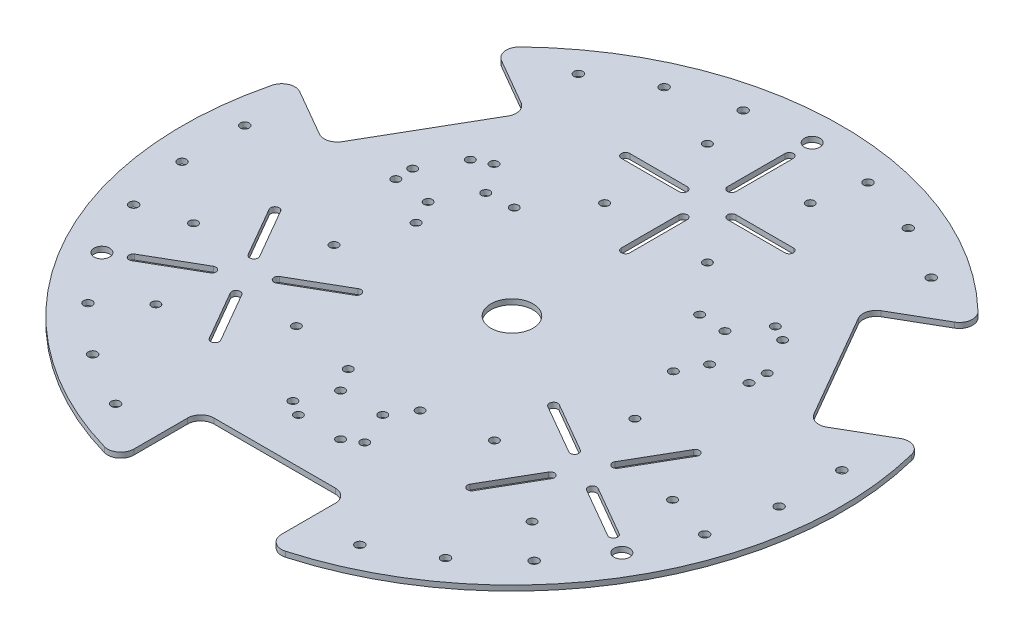
SolidWorks part; units mm, degrees
ref_plane "Front Plane" through (0, 0, 0) normal (0, 0, 1) x (1, 0, 0)
ref_plane "Top Plane" through (0, 0, 0) normal (0, 1, 0) x (1, 0, 0)
ref_plane "Right Plane" through (0, 0, 0) normal (1, 0, 0) x (0, 0, -1)
sketch "Sketch1" plane through (0, 0, 0) normal (0, 1, 0) x (1, 0, 0)
  line L0 (0, 0) -> (0, 125) construction
  line L1 (0, 0) -> (-17.3205, 10) construction
  line L2 (-89.4423, 25.0814) -> (-66.4423, 64.9186)
  line L3 (-68.2724, 71.7487) -> (-91.5024, 85.1605)
  line L4 (-96.2724, 23.2513) -> (-119.5024, 36.6631)
  line L5 (96.2724, 23.2513) -> (119.5024, 36.6631)
  line L6 (66.4423, 64.9186) -> (89.4423, 25.0814)
  line L7 (68.2724, 71.7487) -> (91.5024, 85.1605)
  line L8 (-28, -95) -> (-28, -121.8236)
  line L9 (23, -90) -> (-23, -90)
  line L10 (28, -95) -> (28, -121.8236)
  line L11 (-13.625, -48.465) -> (13.625, -48.465) construction
  line L12 (0, 0) -> (77.9423, 45) construction
  line L13 (0, 0) -> (-108.2532, -62.5) construction
  line L14 (-72.1832, -41.675) -> (-91.0626, -52.575) construction
  line L15 (-71.3832, -43.0606) -> (-90.2626, -53.9606)
  line L16 (-72.9832, -40.2894) -> (-91.8626, -51.1894)
  line L17 (-37.3257, -21.55) -> (-56.205, -32.45) construction
  line L18 (-36.5257, -22.9356) -> (-55.405, -33.8356)
  line L19 (-38.1257, -20.1644) -> (-57.005, -31.0644)
  line L20 (-72.1832, -41.675) -> (-56.205, -32.45) construction
  line L21 (-72.1832, -41.675) -> (-56.205, -32.45) construction
  line L22 (-68.8066, -29.0734) -> (-79.7066, -10.1941) construction
  line L23 (-70.1923, -29.8734) -> (-81.0923, -10.9941)
  line L24 (-67.421, -28.2734) -> (-78.321, -9.3941)
  line L25 (-56.205, -32.45) -> (-37.3257, -21.55) construction
  line L26 (-57.005, -31.0644) -> (-38.1257, -20.1644)
  line L27 (-55.405, -33.8356) -> (-36.5257, -22.9356)
  line L28 (-59.5816, -45.0516) -> (-48.6816, -63.9309) construction
  line L29 (-58.196, -44.2516) -> (-47.296, -63.1309)
  line L30 (-60.9673, -45.8516) -> (-50.0673, -64.7309)
  line L31 (0, 83.35) -> (0, 105.15) construction
  line L32 (-1.6, 83.35) -> (-1.6, 105.15)
  line L33 (1.6, 83.35) -> (1.6, 105.15)
  line L34 (0, 43.1) -> (0, 64.9) construction
  line L35 (-1.6, 43.1) -> (-1.6, 64.9)
  line L36 (1.6, 43.1) -> (1.6, 64.9)
  line L37 (9.225, 74.125) -> (31.025, 74.125) construction
  line L38 (9.225, 75.725) -> (31.025, 75.725)
  line L39 (9.225, 72.525) -> (31.025, 72.525)
  line L40 (-9.225, 74.125) -> (-31.025, 74.125) construction
  line L41 (-9.225, 72.525) -> (-31.025, 72.525)
  line L42 (-9.225, 75.725) -> (-31.025, 75.725)
  line L43 (72.1832, -41.675) -> (91.0626, -52.575) construction
  line L44 (72.9832, -40.2894) -> (91.8626, -51.1894)
  line L45 (71.3832, -43.0606) -> (90.2626, -53.9606)
  line L46 (37.3257, -21.55) -> (56.205, -32.45) construction
  line L47 (38.1257, -20.1644) -> (57.005, -31.0644)
  line L48 (36.5257, -22.9356) -> (55.405, -33.8356)
  line L49 (59.5816, -45.0516) -> (48.6816, -63.9309) construction
  line L50 (60.9673, -45.8516) -> (50.0673, -64.7309)
  line L51 (58.196, -44.2516) -> (47.296, -63.1309)
  line L52 (68.8066, -29.0734) -> (79.7066, -10.1941) construction
  line L53 (67.421, -28.2734) -> (78.321, -9.3941)
  line L54 (70.1923, -29.8734) -> (81.0923, -10.9941)
  line L55 (-49.8802, 55.605) -> (-73.0954, 15.395)
  line L56 (0, 0) -> (0, -90.0676) construction
  line L59 (13.625, -69.465) -> (-13.625, -69.465) construction
  line L60 (-13.625, -48.465) -> (-13.625, -69.465) construction
  line L61 (13.625, -48.465) -> (13.625, -69.465) construction
  line L62 (13.625, -71.065) -> (-13.625, -71.065) construction
  line L63 (8, -57) -> (-8, -57) construction
  line L64 (8, -57) -> (8, -73) construction
  line L65 (8, -73) -> (-8, -73) construction
  line L66 (-8, -57) -> (-8, -73) construction
  line L67 (8, -57) -> (-8, -73) construction
  line L68 (8, -73) -> (-8, -57) construction
  line L69 (8, -74.6) -> (-8, -74.6) construction
  circle A0 centre (0, 0) radius 8
  arc A1 (-119.5024, 36.6631) -> (-28, -121.8236) centre (0, 0) ccw
  circle A2 centre (0, 113.85) radius 2.95
  circle A3 centre (98.597, -56.925) radius 2.95
  circle A4 centre (-98.597, -56.925) radius 2.95
  circle A5 centre (0, 113.85) radius 1.675
  circle A6 centre (0, 0) radius 90 construction
  arc A7 (-89.4423, 25.0814) -> (-96.2724, 23.2513) centre (-93.7724, 27.5814) cw
  arc A8 (-66.4423, 64.9186) -> (-68.2724, 71.7487) centre (-70.7724, 67.4186) ccw
  arc A9 (89.4423, 25.0814) -> (96.2724, 23.2513) centre (93.7724, 27.5814) ccw
  arc A10 (66.4423, 64.9186) -> (68.2724, 71.7487) centre (70.7724, 67.4186) cw
  arc A11 (-23, -90) -> (-28, -95) centre (-23, -95) ccw
  arc A12 (23, -90) -> (28, -95) centre (23, -95) cw
  arc A13 (91.5024, 85.1605) -> (-91.5024, 85.1605) centre (0, 0) ccw
  arc A14 (28, -121.8236) -> (119.5024, 36.6631) centre (0, 0) ccw
  circle A15 centre (23.6707, 111.3621) radius 1.675
  circle A16 centre (46.307, 104.0072) radius 1.675
  circle A17 centre (66.9194, 92.1066) radius 1.675
  circle A18 centre (84.607, 76.1805) radius 1.675
  circle A19 centre (98.597, 56.925) radius 1.675
  circle A20 centre (108.2778, 35.1816) radius 1.675
  circle A21 centre (113.2263, 11.9006) radius 1.675
  circle A22 centre (113.2263, -11.9006) radius 1.675
  circle A23 centre (108.2778, -35.1816) radius 1.675
  circle A25 centre (84.607, -76.1805) radius 1.675
  circle A26 centre (66.9194, -92.1066) radius 1.675
  circle A27 centre (46.307, -104.0072) radius 1.675
  circle A28 centre (23.6707, -111.3621) radius 1.675
  circle A29 centre (0, -113.85) radius 1.675
  circle A30 centre (-23.6707, -111.3621) radius 1.675
  circle A31 centre (-46.307, -104.0072) radius 1.675
  circle A32 centre (-66.9194, -92.1066) radius 1.675
  circle A33 centre (-84.607, -76.1805) radius 1.675
  circle A35 centre (-108.2778, -35.1816) radius 1.675
  circle A36 centre (-113.2263, -11.9006) radius 1.675
  circle A37 centre (-113.2263, 11.9006) radius 1.675
  circle A38 centre (-108.2778, 35.1816) radius 1.675
  circle A39 centre (-98.597, 56.925) radius 1.675
  circle A40 centre (-84.607, 76.1805) radius 1.675
  circle A41 centre (-66.9194, 92.1066) radius 1.675
  circle A42 centre (-46.307, 104.0072) radius 1.675
  circle A43 centre (-23.6707, 111.3621) radius 1.675
  circle A44 centre (-98.597, -56.925) radius 1.675 [skipped]
  circle A45 centre (98.597, -56.925) radius 1.675 [skipped]
  circle A46 centre (0, 0) radius 106.75 construction
  arc A47 (-71.3832, -43.0606) -> (-72.9832, -40.2894) centre (-72.1832, -41.675) ccw
  arc A48 (-91.8626, -51.1894) -> (-90.2626, -53.9606) centre (-91.0626, -52.575) ccw
  circle A49 centre (0, 0) radius 66.5 construction
  arc A50 (-36.5257, -22.9356) -> (-38.1257, -20.1644) centre (-37.3257, -21.55) ccw
  arc A51 (-57.005, -31.0644) -> (-55.405, -33.8356) centre (-56.205, -32.45) ccw
  circle A52 centre (-64.1941, -37.0625) radius 2 construction
  arc A53 (-70.1923, -29.8734) -> (-67.421, -28.2734) centre (-68.8066, -29.0734) ccw
  arc A54 (-78.321, -9.3941) -> (-81.0923, -10.9941) centre (-79.7066, -10.1941) ccw
  arc A55 (-57.005, -31.0644) -> (-55.405, -33.8356) centre (-56.205, -32.45) ccw
  arc A56 (-36.5257, -22.9356) -> (-38.1257, -20.1644) centre (-37.3257, -21.55) ccw
  arc A57 (-58.196, -44.2516) -> (-60.9673, -45.8516) centre (-59.5816, -45.0516) ccw
  arc A58 (-50.0673, -64.7309) -> (-47.296, -63.1309) centre (-48.6816, -63.9309) ccw
  arc A59 (-1.6, 83.35) -> (1.6, 83.35) centre (0, 83.35) ccw
  arc A60 (1.6, 105.15) -> (-1.6, 105.15) centre (0, 105.15) ccw
  arc A61 (-1.6, 43.1) -> (1.6, 43.1) centre (0, 43.1) ccw
  arc A62 (1.6, 64.9) -> (-1.6, 64.9) centre (0, 64.9) ccw
  arc A63 (9.225, 75.725) -> (9.225, 72.525) centre (9.225, 74.125) ccw
  arc A64 (31.025, 72.525) -> (31.025, 75.725) centre (31.025, 74.125) ccw
  arc A65 (-9.225, 72.525) -> (-9.225, 75.725) centre (-9.225, 74.125) ccw
  arc A66 (-31.025, 75.725) -> (-31.025, 72.525) centre (-31.025, 74.125) ccw
  arc A67 (72.9832, -40.2894) -> (71.3832, -43.0606) centre (72.1832, -41.675) ccw
  arc A68 (90.2626, -53.9606) -> (91.8626, -51.1894) centre (91.0626, -52.575) ccw
  arc A69 (38.1257, -20.1644) -> (36.5257, -22.9356) centre (37.3257, -21.55) ccw
  arc A70 (55.405, -33.8356) -> (57.005, -31.0644) centre (56.205, -32.45) ccw
  arc A71 (60.9673, -45.8516) -> (58.196, -44.2516) centre (59.5816, -45.0516) ccw
  arc A72 (47.296, -63.1309) -> (50.0673, -64.7309) centre (48.6816, -63.9309) ccw
  arc A73 (67.421, -28.2734) -> (70.1923, -29.8734) centre (68.8066, -29.0734) ccw
  arc A74 (81.0923, -10.9941) -> (78.321, -9.3941) centre (79.7066, -10.1941) ccw
  circle A75 centre (0, 0) radius 100.95 construction
  circle A76 centre (-61.4878, 35.5) radius 5 construction
  circle A77 centre (-90.8316, -29.925) radius 1.6
  circle A78 centre (-57.0566, -10.425) radius 1.6
  circle A79 centre (-37.5566, -44.2) radius 1.6
  circle A80 centre (-71.3316, -63.7) radius 1.6
  circle A81 centre (19.5, 93.625) radius 1.6
  circle A82 centre (19.5, 54.625) radius 1.6
  circle A83 centre (-19.5, 54.625) radius 1.6
  circle A84 centre (-19.5, 93.625) radius 1.6
  circle A85 centre (71.3316, -63.7) radius 1.6
  circle A86 centre (37.5566, -44.2) radius 1.6
  circle A87 centre (57.0566, -10.425) radius 1.6
  circle A88 centre (90.8316, -29.925) radius 1.6
  circle A89 centre (0, 0) radius 69.465 construction
  circle A90 centre (-13.625, -48.465) radius 1.6
  circle A91 centre (13.625, -48.465) radius 1.6
  circle A92 centre (13.625, -69.465) radius 1.6
  circle A93 centre (-13.625, -69.465) radius 1.6
  circle A94 centre (-35.1594, 36.0321) radius 1.6
  circle A95 centre (-48.7844, 12.4329) radius 1.6
  circle A96 centre (-66.971, 22.9329) radius 1.6
  circle A97 centre (-53.346, 46.5321) radius 1.6
  circle A98 centre (48.7844, 12.4329) radius 1.6
  circle A99 centre (35.1594, 36.0321) radius 1.6
  circle A100 centre (53.346, 46.5321) radius 1.6
  circle A101 centre (66.971, 22.9329) radius 1.6
  circle A102 centre (0, 0) radius 73 construction
  circle A103 centre (-8, -73) radius 1.6
  circle A104 centre (-8, -57) radius 1.6
  circle A105 centre (8, -57) radius 1.6
  circle A106 centre (8, -73) radius 1.6
  circle A107 centre (-59.2199, 43.4282) radius 1.6
  circle A108 centre (-45.3634, 35.4282) radius 1.6
  circle A109 centre (-53.3634, 21.5718) radius 1.6
  circle A110 centre (-67.2199, 29.5718) radius 1.6
  circle A111 centre (67.2199, 29.5718) radius 1.6
  circle A112 centre (53.3634, 21.5718) radius 1.6
  circle A113 centre (45.3634, 35.4282) radius 1.6
  circle A114 centre (59.2199, 43.4282) radius 1.6
  point P14 (0, 0)
  point P18 (-77.9423, 45)
  point P22 (-91.9423, 20.7513)
  point P25 (-63.9423, 69.2487)
  point P44 (0, 0)
  point P84 (-81.6229, -47.125)
  point P103 (0, 0)
  point P115 (-46.7654, -27)
  point P129 (-74.2566, -19.6337)
  point P136 (-46.7654, -27)
  point P143 (-54.1316, -54.4913)
  point P148 (-64.1941, -37.0625)
  point P150 (0, 94.25)
  point P157 (0, 54)
  point P164 (20.125, 74.125)
  point P171 (-20.125, 74.125)
  point P178 (81.6229, -47.125)
  point P185 (46.7654, -27)
  point P192 (54.1316, -54.4913)
  point P199 (74.2566, -19.6337)
  point P204 (0, 0)
  point P209 (-61.4878, 35.5)
  point P220 (-64.1941, -37.0625)
  point P237 (0, 0)
  point P245 (0, -65)
  point P264 (0, 0)
  point P295 (0, 0)
  dimension "D1" = 250
  dimension "D2" = 16
  dimension "D3" = 113.85
  dimension "D4" = 3
  dimension "D5" = 3.35
  dimension "D6" = 60
  dimension "D8" = 5
  dimension "D12" = 213.5
  dimension "D13" = 3.2
  dimension "D14" = 21.8
  dimension "D15" = 3.2
  dimension "D16" = 133
  dimension "D18" = 4
  dimension "D20" = 19
  dimension "D21" = 3.2
  dimension "D26" = 138.93
  dimension "D28" = 3.2
  dimension "D31" = 90
  dimension "D32" = 146
  dimension "D35" = 3.2
  dimension "D37" = 3
  dimension "D7" = 56
  dimension "D11" = 60
  dimension "D17" = 21.8
  dimension "D22" = 17.9
  dimension "D23" = 17.9
  dimension "D27" = 21
  dimension "D29" = 27.25
  dimension "D33" = 16
  dimension "D34" = 16
  dimension "D36" = 15.4
  dimension "D9" = 3
  dimension "D10" = 30
  dimension "D19" = 3
  dimension "D24" = 4
  dimension "D25" = 3
  dimension "D30" = 3
extrude "Boss-Extrude2" add sketch "Sketch1" along normal blind 2
fillet "Fillet1" radius 5 6 edges at (91.5024, 1, -85.1605) (119.5024, 1, -36.6631) (28, 1, 121.8236) (-28, 1, 121.8236) (-119.5024, 1, -36.6631) (-91.5024, 1, -85.1605)
